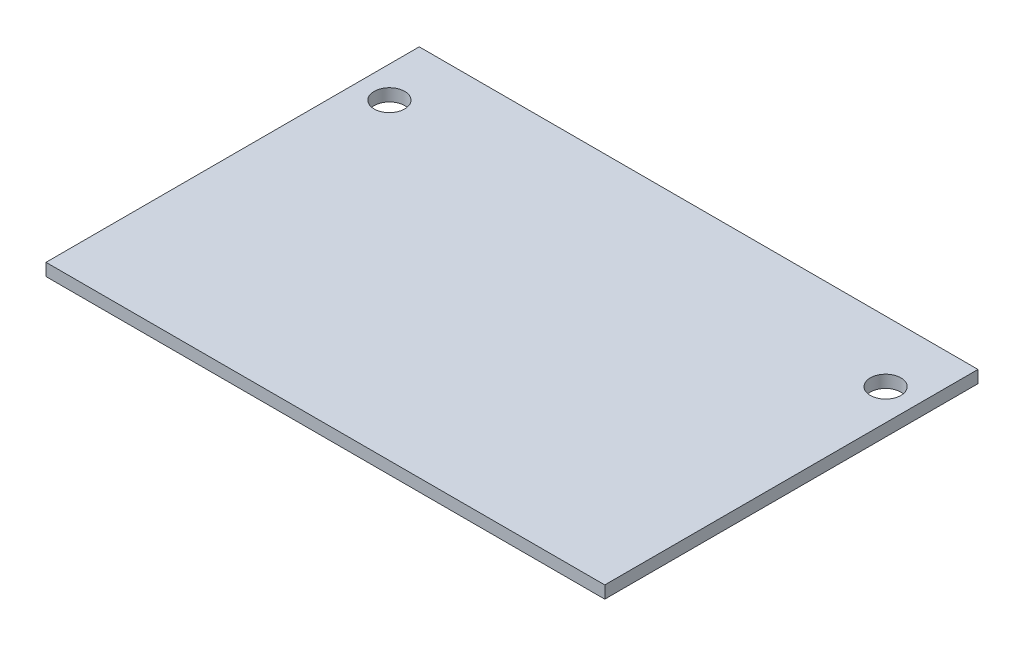
SolidWorks part; units mm, degrees
ref_plane "Front Plane" through (0, 0, 0) normal (0, 0, 1) x (1, 0, 0)
ref_plane "Top Plane" through (0, 0, 0) normal (0, 1, 0) x (1, 0, 0)
ref_plane "Right Plane" through (0, 0, 0) normal (1, 0, 0) x (0, 0, -1)
sketch "Sketch1" plane through (0, 0, 0) normal (0, 1, 0) x (1, 0, 0)
  line L1 (-38.4, 25.65) -> (38.4, 25.65)
  line L2 (-38.4, 25.65) -> (-38.4, -25.65)
  line L3 (-38.4, -25.65) -> (38.4, -25.65)
  line L4 (38.4, 25.65) -> (38.4, -25.65)
  line L5 (-38.4, 25.65) -> (38.4, -25.65) construction
  line L6 (-38.4, -25.65) -> (38.4, 25.65) construction
  point P0 (0, 0)
  dimension "D1" = 76.8
  dimension "D2" = 51.3
extrude "Boss-Extrude1" add sketch "Sketch1" along normal blind 1.7
sketch "Sketch2" plane through (0, 1.7, 0) normal (0, 1, 0) x (1, 0, 0)
  line L0 (38.4, -25.65) -> (38.4, 25.65) construction
  line L1 (38.4, 25.65) -> (-38.4, 25.65) construction
  line L2 (0, -0.935) -> (0, 0.935) construction
  circle A0 centre (34.1, 17.25) radius 2.1
  circle A1 centre (-34.1, 17.25) radius 2.1
  dimension "D1" = 4.2
  dimension "D2" = 4.3
  dimension "D3" = 8.4
extrude "Cut-Extrude1" cut sketch "Sketch2" against normal through all
